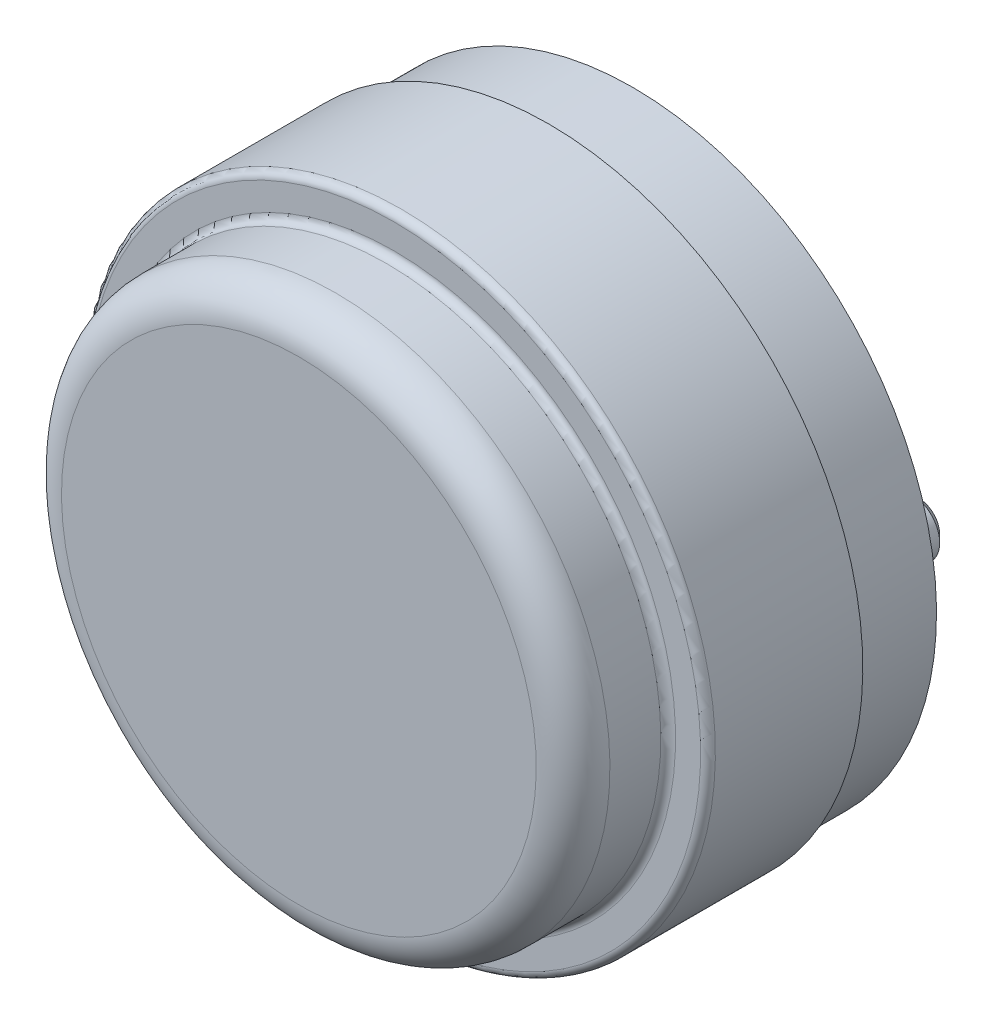
SolidWorks part; units mm, degrees
material "PP Copolymer"
ref_plane "Front Plane" through (0, 0, 0) normal (0, 0, 1) x (1, 0, 0)
ref_plane "Top Plane" through (0, 0, 0) normal (0, 1, 0) x (1, 0, 0)
ref_plane "Right Plane" through (0, 0, 0) normal (1, 0, 0) x (0, 0, -1)
sketch "Sketch2" plane through (0, 0, 0) normal (1, 0, 0) x (0, 0, -1)
  line L0 (0, 0) -> (-7.62, 0) construction
  line L1 (-7.62, 0) -> (-11.5062, 0) construction
  line L2 (-7.62, 0) -> (-11.5062, 0)
  line L33 (-11.5062, 8.1788) -> (-11.5062, 0)
  line L34 (-8.4836, 9.4488) -> (-10.2362, 9.4488)
  line L35 (-8.2296, 10.5664) -> (-8.2296, 9.7028)
  line L36 (-2.8956, 10.8204) -> (-7.9756, 10.8204)
  line L37 (-2.8956, 10.4648) -> (-2.8956, 10.8204)
  line L38 (0, 10.4648) -> (-2.8956, 10.4648)
  line L39 (0, 5.08) -> (0, 10.4648)
  line L40 (-7.62, 5.08) -> (0, 5.08)
  line L41 (-7.62, 0) -> (-7.62, 5.08)
  arc A13 (-10.2362, 9.4488) -> (-11.5062, 8.1788) centre (-10.2362, 8.1788) ccw
  arc A14 (-8.4836, 9.4488) -> (-8.2296, 9.7028) centre (-8.4836, 9.7028) ccw
  arc A15 (-7.9756, 10.8204) -> (-8.2296, 10.5664) centre (-7.9756, 10.5664) ccw
  dimension "D4" = 1.27
  dimension "D5" = 0.254
  dimension "D7" = 0.254
  dimension "D1" = 7.62
  dimension "D2" = 8.1788
  dimension "D3" = 3.8862
  dimension "D6" = 3.2766
  dimension "D8" = 1.3716
  dimension "D9" = 5.08
  dimension "D10" = 0.3556
  dimension "D11" = 5.3848
  dimension "D12" = 2.8956
revolve "Revolve1" add sketch "Sketch2" angle 360 about L0
sketch "Sketch3" plane through (0, 0, 0) normal (0, 0, 1) x (1, 0, 0)
  line L0 (0, 0) -> (0, -12.1371) construction
  line L1 (7.4422, 0) -> (0, 0) construction
  circle A1 centre (7.4422, 0) radius 0.9716
  circle A2 centre (-7.4422, 0) radius 0.9716
  dimension "D1" = 1.9431
  dimension "D2" = 7.4422
extrude "Extrude2" add sketch "Sketch3" against normal blind 2.41
chamfer "Chamfer1" distance 0.25 angle 45 2 edges at (8.4138, 0, -2.41) (-8.4138, 0, -2.41)
